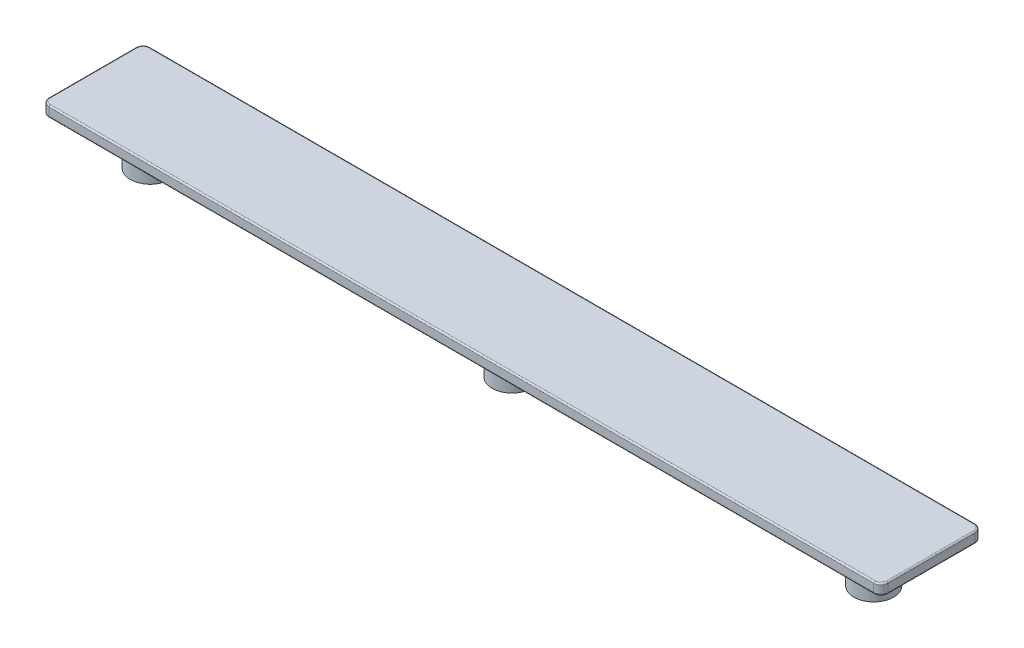
SolidWorks part; units mm, degrees
ref_plane "Front Plane" through (0, 0, 0) normal (0, 0, 1) x (1, 0, 0)
ref_plane "Top Plane" through (0, 0, 0) normal (0, 1, 0) x (1, 0, 0)
ref_plane "Right Plane" through (0, 0, 0) normal (1, 0, 0) x (0, 0, -1)
sketch "Sketch1" plane through (0, 0, 0) normal (0, 1, 0) x (1, 0, 0)
  line L1 (-109.3247, 4.3967) -> (4.6753, 4.3967)
  line L2 (-110.3247, 3.3967) -> (-110.3247, -8.6033)
  line L3 (-109.3247, -9.6033) -> (4.6753, -9.6033)
  line L4 (5.6753, 3.3967) -> (5.6753, -8.6033)
  arc A0 (-110.3247, -8.6033) -> (-109.3247, -9.6033) centre (-109.3247, -8.6033) ccw
  arc A1 (4.6753, -9.6033) -> (5.6753, -8.6033) centre (4.6753, -8.6033) ccw
  arc A2 (4.6753, 4.3967) -> (5.6753, 3.3967) centre (4.6753, 3.3967) cw
  arc A3 (-109.3247, 4.3967) -> (-110.3247, 3.3967) centre (-109.3247, 3.3967) ccw
  point P8 (5.6753, -9.6033)
  point P11 (5.6753, 4.3967)
  point P14 (-110.3247, 4.3967)
  dimension "D3" = 1
  dimension "D1" = 116
  dimension "D2" = 14
extrude "Boss-Extrude1" add sketch "Sketch1" along normal blind 1.5
sketch "Sketch2" plane through (0, 0, 0) normal (0, -1, 0) x (1, 0, 0)
  line L0 (-109.3247, 9.6033) -> (4.6753, 9.6033) construction
  line L1 (5.6753, 8.6033) -> (5.6753, -3.3967) construction
  line L2 (-52.3247, -4.3967) -> (-52.3247, 9.6033) construction
  line L3 (-110.3247, 2.6033) -> (5.6753, 2.6033) construction
  line L4 (-110.3247, -3.3967) -> (-110.3247, 8.6033) construction
  line L5 (-102.3247, 9.6033) -> (-102.3247, -4.3967) construction
  line L6 (4.6753, -4.3967) -> (-109.3247, -4.3967) construction
  line L7 (-2.3247, 9.6033) -> (-2.3247, -4.3967) construction
  circle A0 centre (-52.3247, 2.6033) radius 2.75
  circle A1 centre (-102.3247, 2.6033) radius 2.75
  circle A2 centre (-2.3247, 2.6033) radius 2.75
  dimension "D1" = 7
  dimension "D2" = 58
  dimension "D3" = 50
  dimension "D4" = 50
extrude "Boss-Extrude2" add sketch "Sketch2" along normal blind 6
sketch "Sketch3" plane through (0, -6, 0) normal (0, -1, 0) x (1, 0, 0)
  line L0 (-52.3247, 5.3533) -> (-52.3247, -0.1467) construction
  line L1 (-54.3247, 3.1533) -> (-50.3247, 3.1533)
  line L2 (-54.3247, 3.1533) -> (-54.3247, 2.0533)
  line L3 (-54.3247, 2.0533) -> (-50.3247, 2.0533)
  line L4 (-50.3247, 3.1533) -> (-50.3247, 2.0533)
  line L5 (-52.8747, 4.6033) -> (-51.7747, 4.6033)
  line L6 (-52.8747, 4.6033) -> (-52.8747, 0.6033)
  line L7 (-52.8747, 0.6033) -> (-51.7747, 0.6033)
  line L8 (-51.7747, 4.6033) -> (-51.7747, 0.6033)
  line L9 (-55.0747, 2.6033) -> (-49.5747, 2.6033) construction
  line L10 (-102.3247, 5.3533) -> (-102.3247, -0.1467) construction
  line L15 (-99.5747, 2.6033) -> (-105.0747, 2.6033) construction
  line L16 (-2.537, 5.3451) -> (-2.537, -0.1385) construction
  line L17 (-102.8747, 4.6033) -> (-101.7747, 4.6033)
  line L18 (-102.8747, 4.6033) -> (-102.8747, 0.6033)
  line L19 (-102.8747, 0.6033) -> (-101.7747, 0.6033)
  line L20 (-101.7747, 4.6033) -> (-101.7747, 0.6033)
  line L21 (-104.3247, 3.1533) -> (-100.3247, 3.1533)
  line L22 (-104.3247, 3.1533) -> (-104.3247, 2.0533)
  line L23 (-104.3247, 2.0533) -> (-100.3247, 2.0533)
  line L24 (-100.3247, 3.1533) -> (-100.3247, 2.0533)
  line L25 (-5.0747, 2.6033) -> (0.4253, 2.6033) construction
  line L27 (-3.087, 4.6033) -> (-1.987, 4.6033)
  line L28 (-3.087, 4.6033) -> (-3.087, 0.6033)
  line L29 (-3.087, 0.6033) -> (-1.987, 0.6033)
  line L30 (-1.987, 4.6033) -> (-1.987, 0.6033)
  line L31 (-4.537, 3.1533) -> (-0.537, 3.1533)
  line L32 (-4.537, 3.1533) -> (-4.537, 2.0533)
  line L33 (-4.537, 2.0533) -> (-0.537, 2.0533)
  line L34 (-0.537, 3.1533) -> (-0.537, 2.0533)
  circle A0 centre (-102.3247, 2.6033) radius 2.75 construction
  circle A1 centre (-2.3247, 2.6033) radius 2.75 construction
  circle A3 centre (-52.3247, 2.6033) radius 2.75 construction
  circle A4 centre (-52.3247, 2.6033) radius 2.75 construction
  dimension "D7" = 0.55
  dimension "D1" = 4
  dimension "D2" = 1.1
  dimension "D3" = 1.1
  dimension "D4" = 4
  dimension "D5" = 2
  dimension "D6" = 2
  dimension "D8" = 0.55
  dimension "D9" = 4
  dimension "D10" = 4
  dimension "D11" = 1.1
  dimension "D12" = 1.1
  dimension "D13" = 2
  dimension "D14" = 2
  dimension "D15" = 0.55
  dimension "D16" = 0.55
  dimension "D17" = 4
  dimension "D18" = 1.1
  dimension "D19" = 1.1
  dimension "D21" = 0.55
  dimension "D22" = 0.55
  dimension "D23" = 2
  dimension "D24" = 2
  dimension "D25" = 4
extrude "Cut-Extrude1" cut sketch "Sketch3" against normal blind 6 contours L8 L5 L6 L1 | L1 L8 L3 L4 | L8 L1 L6 L3 | L6 L1 L2 L3 | L8 L3 L6 L7 | L32 L31 L34 L33 | L28 L27 L30 L29 | L18 L17 L20 L19 | L22 L21 L24 L23
chamfer "Chamfer1" distance 0.3 angle 45 36 edges at (-52.3247, -6, 0.6033) (-52.8747, -6, 1.3283) (-53.5997, -6, 2.0533) (-54.3247, -6, 2.6033) (-53.5997, -6, 3.1533) (-51.7747, -6, 1.3283) (-51.0497, -6, 2.0533) (-50.3247, -6, 2.6033) (-51.0497, -6, 3.1533) (-51.7747, -6, 3.8783) (-52.3247, -6, 4.6033) (-52.8747, -6, 3.8783) (-102.3247, -6, 4.6033) (-102.8747, -6, 3.8783) (-103.5997, -6, 3.1533) (-104.3247, -6, 2.6033) (-103.5997, -6, 2.0533) (-102.8747, -6, 1.3283) (-102.3247, -6, 0.6033) (-101.7747, -6, 1.3283) (-101.0497, -6, 2.0533) (-100.3247, -6, 2.6033) (-101.0497, -6, 3.1533) (-101.7747, -6, 3.8783) (-3.087, -6, 3.8783) (-3.812, -6, 3.1533) (-4.537, -6, 2.6033) (-3.812, -6, 2.0533) (-3.087, -6, 1.3283) (-2.537, -6, 0.6033) (-1.987, -6, 1.3283) (-1.262, -6, 2.0533) (-0.537, -6, 2.6033) (-1.262, -6, 3.1533) (-1.987, -6, 3.8783) (-2.537, -6, 4.6033)
fillet "Fillet1" radius 1 3 edges at (-52.3247, 0, 5.3533) (-2.3247, 0, 5.3533) (-102.3247, 0, 5.3533)
fillet "Fillet3" radius 0.2 16 edges at (5.3824, 1.5, -4.1038) (5.6753, 1.5, 2.6033) (5.3824, 1.5, 9.3104) (-52.3247, 1.5, 9.6033) (-110.0318, 1.5, 9.3104) (-110.0318, 1.5, -4.1038) (-110.3247, 1.5, 2.6033) (-52.3247, 1.5, -4.3967) (5.3824, 0, 9.3104) (5.6753, 0, 2.6033) (5.3824, 0, -4.1038) (-52.3247, 0, -4.3967) (-110.0318, 0, -4.1038) (-110.3247, 0, 2.6033) (-110.0318, 0, 9.3104) (-52.3247, 0, 9.6033)
